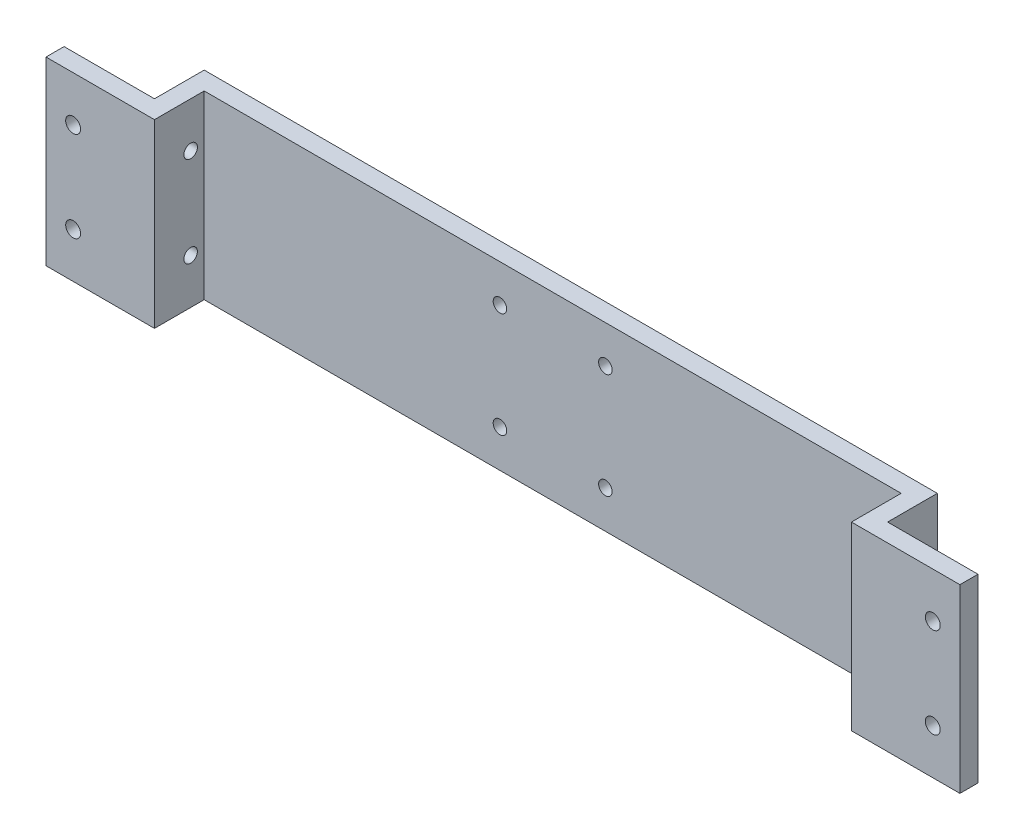
SolidWorks part; units mm, degrees
ref_plane "Front Plane" through (0, 0, 0) normal (0, 0, 1) x (1, 0, 0)
ref_plane "Top Plane" through (0, 0, 0) normal (0, 1, 0) x (1, 0, 0)
ref_plane "Right Plane" through (0, 0, 0) normal (1, 0, 0) x (0, 0, -1)
sketch "Sketch1" plane through (0, 0, 0) normal (0, 0, 1) x (1, 0, 0)
  line L0 (0, 35.1273) -> (0, -34.9325) construction
  line L1 (-101.1, 20) -> (101.1, 20)
  line L2 (-101.1, 20) -> (-101.1, -20)
  line L3 (-101.1, -20) -> (101.1, -20)
  line L4 (101.1, 20) -> (101.1, -20)
  line L5 (-101.1, 20) -> (101.1, -20) construction
  line L6 (-101.1, -20) -> (101.1, 20) construction
  circle A0 centre (-95.1, 10) radius 1.65
  circle A2 centre (-95.1, -10) radius 1.65
  circle A3 centre (95.1, -10) radius 1.65
  circle A4 centre (95.1, 10) radius 1.65
  point P0 (0, 0)
  point P6 (0, 0)
  dimension "D4" = 3.3
  dimension "D5" = 6
  dimension "D6" = 10
  dimension "D8" = 3.3
  dimension "D9" = 6
  dimension "D10" = 10
  dimension "D1" = 202.2
  dimension "D2" = 40
extrude "Boss-Extrude1" add sketch "Sketch1" along normal blind 4
sketch "Sketch2" plane through (0, 0, 4) normal (0, 0, 1) x (1, 0, 0)
  line L0 (-101.1, -20) -> (101.1, -20) construction
  line L5 (-81.1, 20) -> (81.1, 20)
  line L6 (-81.1, 20) -> (-81.1, -20)
  line L7 (0, 53.9019) -> (0, -40.6772) construction
  line L8 (-81.1, -20) -> (81.1, -20)
  line L9 (81.1, 20) -> (81.1, -20)
  line L10 (-81.1, 20) -> (81.1, -20) construction
  line L11 (-81.1, -20) -> (81.1, 20) construction
  line L12 (-81.1, 20) -> (-101.1, 20)
  line L13 (-101.1, 20) -> (-101.1, -20)
  line L14 (-101.1, -20) -> (-81.1, -20)
  line L15 (81.1, 20) -> (101.1, 20)
  line L16 (101.1, 20) -> (101.1, -20)
  line L17 (101.1, -20) -> (81.1, -20)
  point P0 (0, 0)
  point P1 (0, 0)
  dimension "D1" = 20
extrude "Cut-Extrude1" cut sketch "Sketch2" against normal blind 4 contours L6 L5 L9 L8
sketch "Sketch3" plane through (0, -20, 0) normal (0, -1, 0) x (1, 0, 0)
  line L0 (-81.1, 4) -> (-77.1, 4)
  line L1 (-77.1, 4) -> (-77.1, -7)
  line L2 (-77.1, -7) -> (77.1, -7)
  line L3 (77.1, -7) -> (77.1, 4)
  line L4 (77.1, 4) -> (81.1, 4)
  line L5 (81.1, 4) -> (81.1, -11)
  line L6 (81.1, -11) -> (-81.1, -11)
  line L7 (-81.1, -11) -> (-81.1, 4)
  dimension "D1" = 4
  dimension "D2" = 15
  dimension "D3" = 4
  dimension "D4" = 4
extrude "Boss-Extrude3" add sketch "Sketch3" against normal up to surface (40 mm away) up to face at (91.1, 20, 2)
sketch "Sketch4" plane through (-81.1, 0, 0) normal (-1, 0, 0) x (0, 0, 1)
  line L0 (4, 20) -> (4, -20) construction
  line L1 (-11, 20) -> (0, 20) construction
  line L2 (0, -20) -> (-11, -20) construction
  circle A0 centre (-4, 10) radius 1.5
  circle A1 centre (-4, -10) radius 1.5
  dimension "D1" = 3
  dimension "D2" = 8
  dimension "D3" = 10
  dimension "D4" = 8
  dimension "D5" = 10
extrude "Cut-Extrude2" cut sketch "Sketch4" against normal through all both and the other way through all
sketch "Sketch5" plane through (0, 0, -7) normal (0, 0, 1) x (1, 0, 0)
  line L1 (-11.665, -11.665) -> (11.665, -11.665) construction
  line L2 (-11.665, -11.665) -> (-11.665, 11.665) construction
  line L3 (-11.665, 11.665) -> (11.665, 11.665) construction
  line L4 (11.665, -11.665) -> (11.665, 11.665) construction
  line L5 (-11.665, -11.665) -> (11.665, 11.665) construction
  line L6 (-11.665, 11.665) -> (11.665, -11.665) construction
  circle A0 centre (-11.665, 11.665) radius 1.5
  circle A1 centre (11.665, 11.665) radius 1.5
  circle A2 centre (11.665, -11.665) radius 1.5
  circle A3 centre (-11.665, -11.665) radius 1.5
  point P0 (0, 0)
  dimension "D2" = 3
  dimension "D1" = 23.33
  dimension "D3" = 4
extrude "Cut-Extrude3" cut sketch "Sketch5" against normal through all and the other way through all
